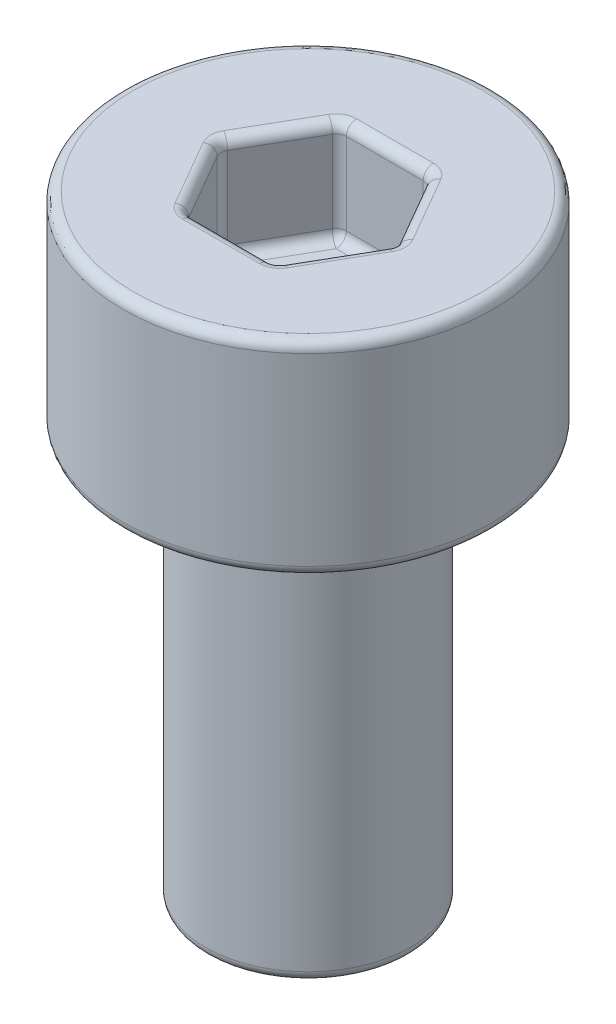
SolidWorks part; units mm, degrees
material "Cast Carbon Steel"
ref_plane "前视基准面" through (0, 0, 0) normal (0, 0, 1) x (1, 0, 0)
ref_plane "上视基准面" through (0, 0, 0) normal (0, 1, 0) x (1, 0, 0)
ref_plane "右视基准面" through (0, 0, 0) normal (1, 0, 0) x (0, 0, -1)
sketch "Sketch1" plane through (0, 0, 0) normal (0, 1, 0) x (1, 0, 0)
  circle A0 centre (0, 0) radius 2
  dimension "螺丝直径" = 4
extrude "Boss-Extrude1" add sketch "Sketch1" against normal blind 8
sketch "Sketch2" plane through (0, 0, 0) normal (0, 1, 0) x (1, 0, 0)
  circle A0 centre (0, 0) radius 3.61
  dimension "头部直径" = 7.22
extrude "Boss-Extrude2" add sketch "Sketch2" along normal blind 4
sketch "Sketch3" plane through (0, 4, 0) normal (0, 1, 0) x (1, 0, 0)
  line L1 (1.7321, 0) -> (0.866, 1.5)
  line L2 (0.866, 1.5) -> (-0.866, 1.5)
  line L3 (-0.866, 1.5) -> (-1.7321, 0)
  line L4 (-1.7321, 0) -> (-0.866, -1.5)
  line L5 (-0.866, -1.5) -> (0.866, -1.5)
  line L6 (0.866, -1.5) -> (1.7321, 0)
  circle A0 centre (0, 0) radius 1.5 construction
  dimension "内六角对边" = 3
extrude "Cut-Extrude1" cut sketch "Sketch3" against normal blind 2
fillet "Fillet1" radius 0.2 21 edges at (-1.299, 2, 0.75) (-1.299, 4, 0.75) (-0.866, 3, 1.5) (0, 2, 1.5) (0, 4, 1.5) (0.866, 3, 1.5) (1.299, 2, 0.75) (1.299, 4, 0.75) (1.7321, 3, 0) (1.299, 2, -0.75) (1.299, 4, -0.75) (-1.299, 2, -0.75) (-1.7321, 3, 0) (-1.299, 4, -0.75) (0.866, 3, -1.5) (0, 2, -1.5) (-0.866, 3, -1.5) (0, 4, -1.5) (0, -8, 2) (0, 0, 3.61) (0, 4, 3.61)
other "冻结***"
